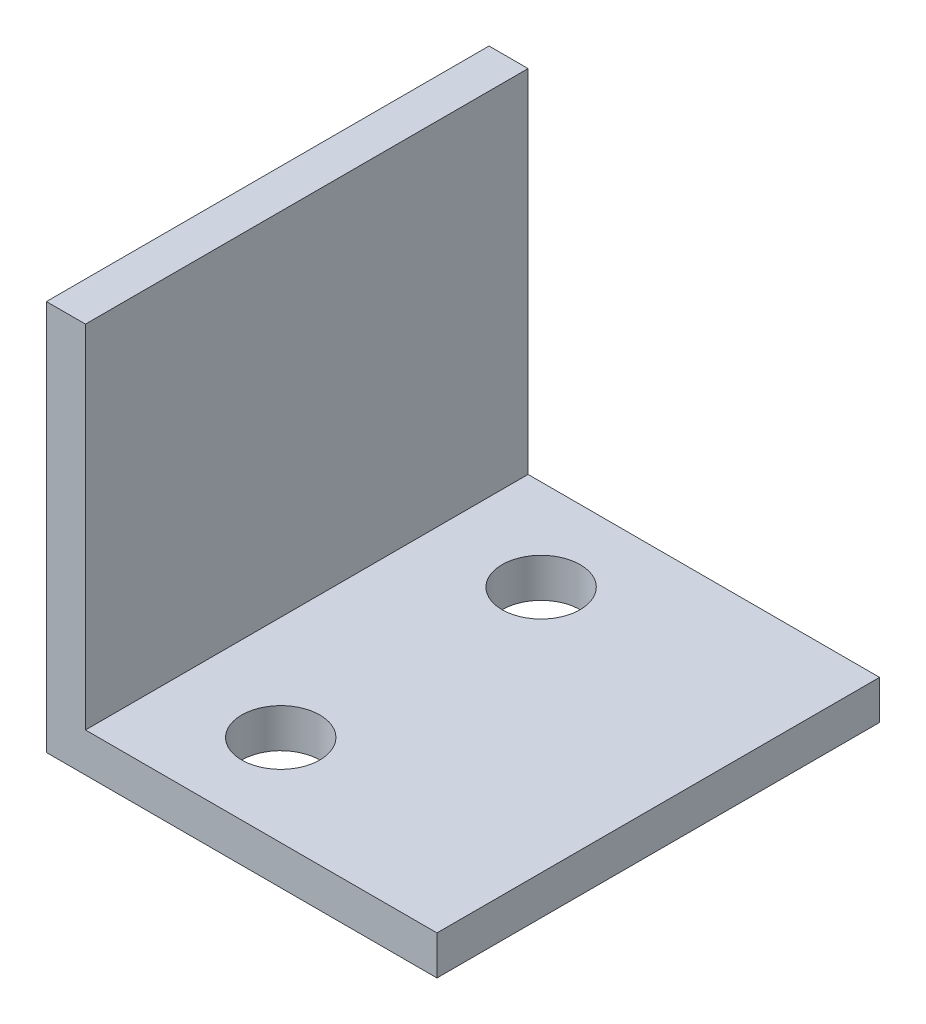
SolidWorks part; units mm, degrees
ref_plane "Plan de face" through (0, 0, 0) normal (0, 0, 1) x (1, 0, 0)
ref_plane "Plan de dessus" through (0, 0, 0) normal (0, 1, 0) x (1, 0, 0)
ref_plane "Plan de droite" through (0, 0, 0) normal (1, 0, 0) x (0, 0, -1)
sketch "Esquisse1" plane through (0, 0, 0) normal (0, 0, 1) x (1, 0, 0)
  line L0 (-21.9769, -4.5446) -> (-21.9769, -19.5446)
  line L1 (-21.9769, -19.5446) -> (-6.9769, -19.5446)
  line L2 (-6.9769, -19.5446) -> (-6.9769, -18.0446)
  line L3 (-6.9769, -18.0446) -> (-20.4769, -18.0446)
  line L4 (-20.4769, -18.0446) -> (-20.4769, -4.5446)
  line L5 (-20.4769, -4.5446) -> (-21.9769, -4.5446)
  dimension "D1" = 15
  dimension "D2" = 1.5
  dimension "D3" = 1.5
  dimension "D4" = 15
extrude "Extrusion1" add sketch "Esquisse1" along normal blind 17
sketch "Esquisse2" plane through (0, -18.0446, 0) normal (0, 1, 0) x (1, 0, 0)
  line L0 (-16.4769, -13.5) -> (-16.4769, -3.5) construction
  line L1 (-6.9769, -17) -> (-20.4769, -17) construction
  line L2 (-6.9769, -17) -> (-6.9769, 0) construction
  circle A0 centre (-16.4769, -13.5) radius 1.5
  circle A1 centre (-16.4769, -3.5) radius 1.5
  dimension "D1" = 10
  dimension "D2" = 3.5
  dimension "D3" = 9.5
extrude "Extrusion2" cut sketch "Esquisse2" against normal blind 15
